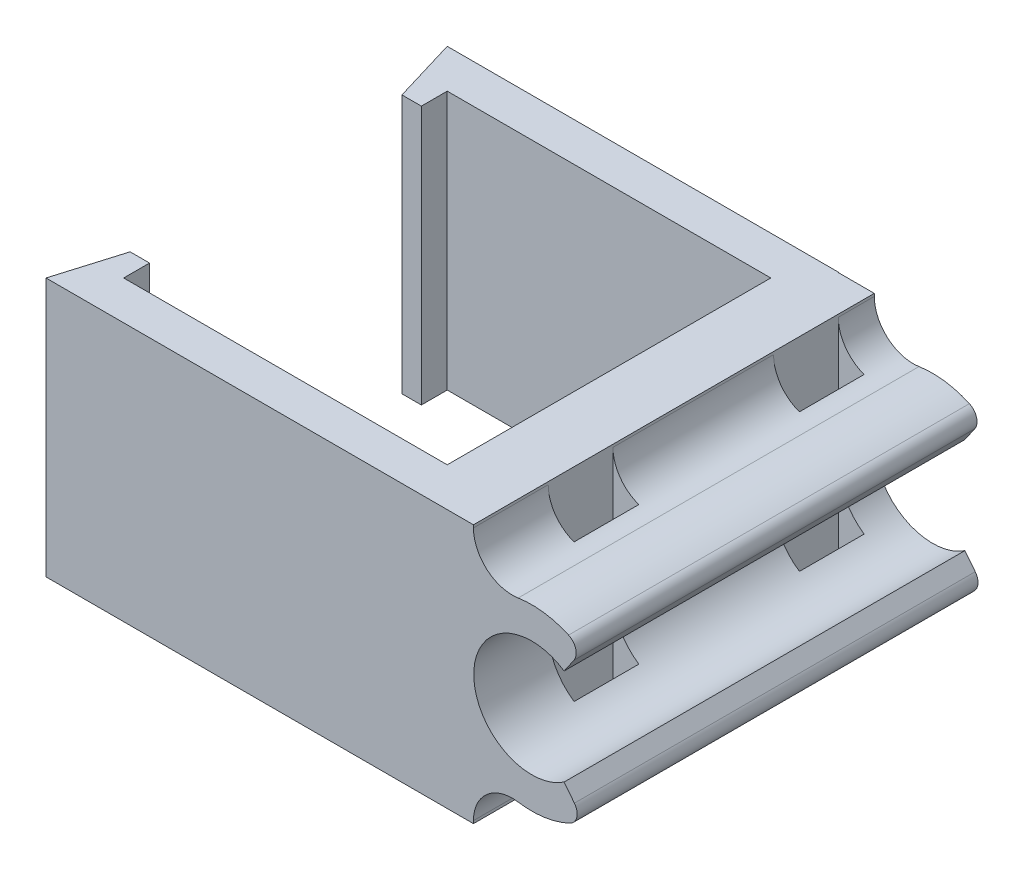
SolidWorks part; units mm, degrees
ref_plane "Спереди" through (0, 0, 0) normal (0, 0, 1) x (1, 0, 0)
ref_plane "Сверху" through (0, 0, 0) normal (0, 1, 0) x (1, 0, 0)
ref_plane "Справа" through (0, 0, 0) normal (1, 0, 0) x (0, 0, -1)
sketch "Эскиз1" plane through (0, 0, 0) normal (0, 1, 0) x (1, 0, 0)
  line L0 (-66.8258, 34.9697) -> (-66.8258, 29.9697)
  line L1 (-63.8258, 29.9697) -> (-63.8258, 31.9697)
  line L2 (-63.8258, 31.9697) -> (-38.8258, 31.9697)
  line L3 (-38.8258, 31.9697) -> (-38.8258, 6.9697)
  line L4 (-38.8258, 6.9697) -> (-63.8258, 6.9697)
  line L5 (-63.8258, 6.9697) -> (-63.8258, 8.9697)
  line L6 (-63.8258, 8.9697) -> (-66.8258, 8.9697)
  line L7 (-66.8258, 8.9697) -> (-66.8258, 3.9697)
  line L8 (-66.8258, 3.9697) -> (-22.1235, 3.9697)
  line L9 (-22.1235, 3.9697) -> (-36.579, 34.9697)
  line L10 (-36.579, 34.9697) -> (-66.8258, 34.9697)
  line L11 (-66.8258, 29.9697) -> (-63.8258, 29.9697)
  dimension "D1" = 25
  dimension "D2" = 25
  dimension "D3" = 25
  dimension "D4" = 155
  dimension "D5" = 3
  dimension "D6" = 3
  dimension "D7" = 3
  dimension "D8" = 3
  dimension "D9" = 2
  dimension "D10" = 2
extrude "Бобышка-Вытянуть1" add sketch "Эскиз1" along normal blind 25
sketch "Эскиз3" plane through (0, 0, 0) normal (0, -1, 0) x (1, 0, 0)
  line L0 (-66.8258, -3.9697) -> (-65.3258, -8.9697)
  line L1 (-63.8258, -8.9697) -> (-66.8258, -8.9697) construction
  line L2 (-65.3258, -8.9697) -> (-66.8258, -8.9697)
  line L3 (-66.8258, -8.9697) -> (-66.8258, -3.9697)
  line L4 (-66.8258, -29.9697) -> (-66.8258, -34.9697)
  line L5 (-66.8258, -34.9697) -> (-65.3258, -29.9697)
  line L6 (-66.8258, -29.9697) -> (-63.8258, -29.9697) construction
  line L7 (-65.3258, -29.9697) -> (-66.8258, -29.9697)
extrude "Вырез-Вытянуть4" cut sketch "Эскиз3" against normal through all
sketch "Эскиз7" plane through (0, 0, 0) normal (0, -1, 0) x (-1, 0, 0)
  line L1 (36.0076, 1.3029) -> (19.3993, 1.3029)
  line L2 (36.0076, 1.3029) -> (36.0076, 39.7765)
  line L3 (36.0076, 39.7765) -> (19.3993, 39.7765)
  line L4 (19.3993, 1.3029) -> (19.3993, 39.7765)
extrude "Вырез-Вытянуть14" cut sketch "Эскиз7" against normal through all
sketch "Эскиз8" plane through (0, 0, 0) normal (0, -1, 0) x (-1, 0, 0)
  line L0 (66.8258, 3.9697) -> (36.0076, 3.9697) construction
  line L1 (38.7989, 3.9697) -> (33.7989, 3.9697)
  line L2 (38.7989, 3.9697) -> (38.7989, 34.9383)
  line L3 (38.7989, 34.9383) -> (33.7989, 34.9383)
  line L4 (33.7989, 3.9697) -> (33.7989, 34.9383)
  dimension "D1" = 5
extrude "Бобышка-Вытянуть2" add sketch "Эскиз8" against normal up to surface (25 mm away) up to face at (-54.2963, 25, -20.5678)
sketch "Эскиз9" plane through (0, 0, -3.9697) normal (0, 0, 1) x (1, 0, 0)
  line L0 (-66.8258, 25) -> (-66.8258, 0) construction
  line L1 (-66.8258, 5) -> (-33.7989, 5)
  line L2 (-66.8258, 5) -> (-66.8258, 0)
  line L3 (-66.8258, 0) -> (-33.7989, 0)
  line L4 (-33.7989, 5) -> (-33.7989, 0)
  line L5 (-66.8258, 0) -> (-33.7989, 0) construction
  dimension "D1" = 5
extrude "Вырез-Вытянуть15" cut sketch "Эскиз9" against normal through all and the other way through all
sketch "Эскиз10" plane through (0, 0, -3.9697) normal (0, 0, 1) x (1, 0, 0)
  line L0 (-33.7989, 15) -> (-22.6548, 15) construction
  line L1 (-33.7989, 25) -> (-33.7989, 5) construction
  line L2 (-29.2989, 24.7662) -> (-29.2989, 5.527) construction
  line L3 (-26.7989, 24.7662) -> (-26.7989, 5.527) construction
  line L4 (-25.4183, 20.7146) -> (-25.2909, 5.7363) construction
  line L5 (-26.7989, 18.714) -> (-25.4183, 20.7146)
  line L6 (-26.7989, 11.286) -> (-25.2909, 9.3741)
  arc A0 (-26.7989, 18.714) -> (-26.7989, 11.286) centre (-29.2989, 15) ccw
  arc A1 (-25.4183, 20.7146) -> (-25.2909, 9.3741) centre (-29.2989, 15) ccw
  dimension "D1" = 4.5
  dimension "D2" = 2.5
extrude "Бобышка-Вытянуть3" add sketch "Эскиз10" against normal up to surface (30.9685 mm away) up to face at (-35.1816, 15, -34.9383)
fillet "Скругление1" radius 3 2 edges at (-33.7989, 20.2407, -19.454) (-33.7989, 9.7593, -19.454)
fillet "Скругление2" radius 1 2 edges at (-25.4183, 20.7146, -19.454) (-25.2909, 9.3741, -19.454)
sketch "Эскиз11" plane through (0, 5, 0) normal (0, -1, 0) x (1, 0, 0)
  line L0 (-33.7989, -34.9383) -> (-33.7989, -3.9697) construction
  line L1 (-33.7989, -9.7447) -> (-31.7989, -9.7447)
  line L2 (-33.7989, -9.7447) -> (-33.7989, -14.7447)
  line L3 (-33.7989, -14.7447) -> (-31.7989, -14.7447)
  line L4 (-31.7989, -9.7447) -> (-31.7989, -14.7447)
  line L5 (-33.7989, -34.9383) -> (-33.7989, -3.9697) construction
  line L6 (-33.7989, -27.1543) -> (-31.7989, -27.1543)
  line L7 (-33.7989, -27.1543) -> (-33.7989, -32.1543)
  line L8 (-33.7989, -32.1543) -> (-31.7989, -32.1543)
  line L9 (-31.7989, -27.1543) -> (-31.7989, -32.1543)
  dimension "D1" = 2
  dimension "D2" = 2
  dimension "D3" = 5
  dimension "D4" = 5
extrude "Вырез-Вытянуть16" cut sketch "Эскиз11" against normal through all
